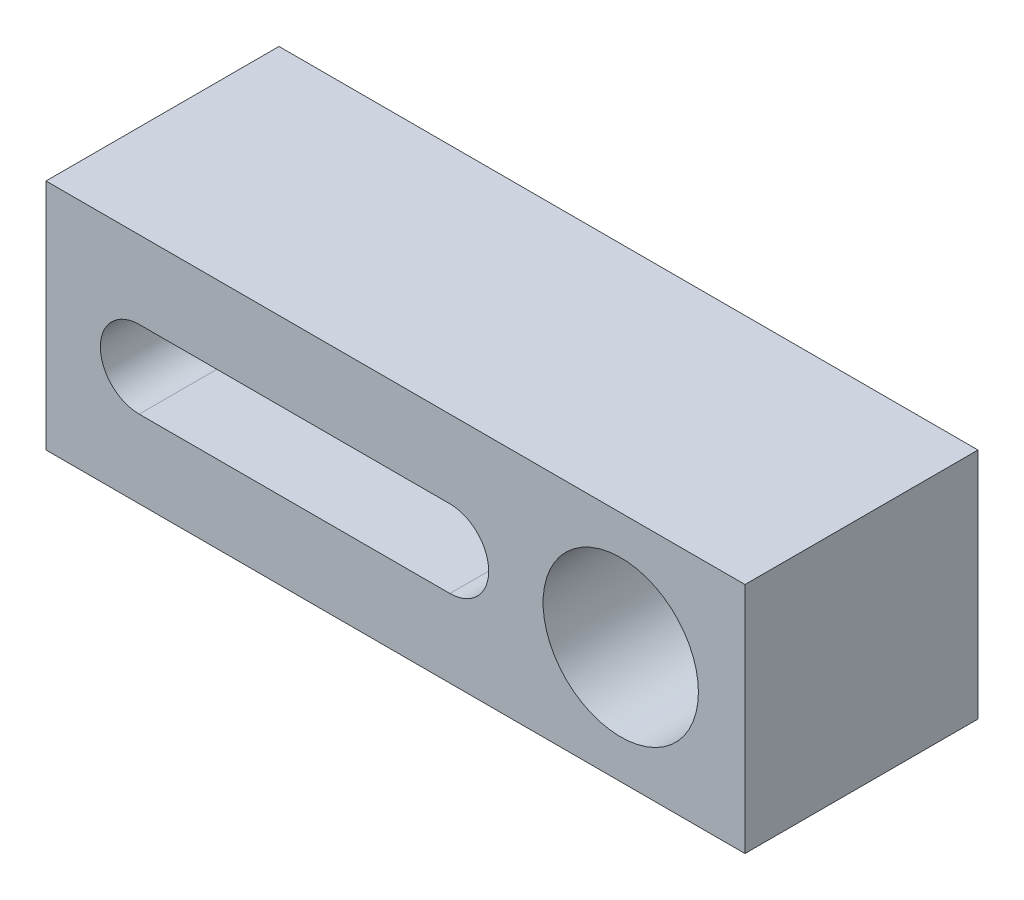
SolidWorks part; units mm, degrees
ref_plane "Front Plane" through (0, 0, 0) normal (0, 0, 1) x (1, 0, 0)
ref_plane "Top Plane" through (0, 0, 0) normal (0, 1, 0) x (1, 0, 0)
ref_plane "Right Plane" through (0, 0, 0) normal (1, 0, 0) x (0, 0, -1)
sketch "Sketch1" plane through (0, 0, 0) normal (0, 0, 1) x (1, 0, 0)
  line L0 (0, 0) -> (-22.5, 0) construction
  line L1 (22.5, -7.5) -> (-22.5, -7.5)
  line L2 (22.5, -7.5) -> (22.5, 7.5)
  line L3 (22.5, 7.5) -> (-22.5, 7.5)
  line L4 (-22.5, -7.5) -> (-22.5, 7.5)
  line L5 (22.5, -7.5) -> (-22.5, 7.5) construction
  line L6 (22.5, 7.5) -> (-22.5, -7.5) construction
  line L7 (3.5, 0) -> (-16.5, 0) construction
  line L8 (3.5, -2.5) -> (-16.5, -2.5)
  line L9 (3.5, 2.5) -> (-16.5, 2.5)
  arc A0 (3.5, -2.5) -> (3.5, 2.5) centre (3.5, 0) ccw
  arc A1 (-16.5, 2.5) -> (-16.5, -2.5) centre (-16.5, 0) ccw
  circle A2 centre (14.5, 0) radius 5
  point P0 (0, 0)
  point P10 (-6.5, 0)
  dimension "D6" = 10
  dimension "D1" = 15
  dimension "D2" = 45
  dimension "D3" = 5
  dimension "D4" = 16
  dimension "D5" = 20
  dimension "D7" = 8
extrude "Boss-Extrude1" add sketch "Sketch1" along normal blind 15
